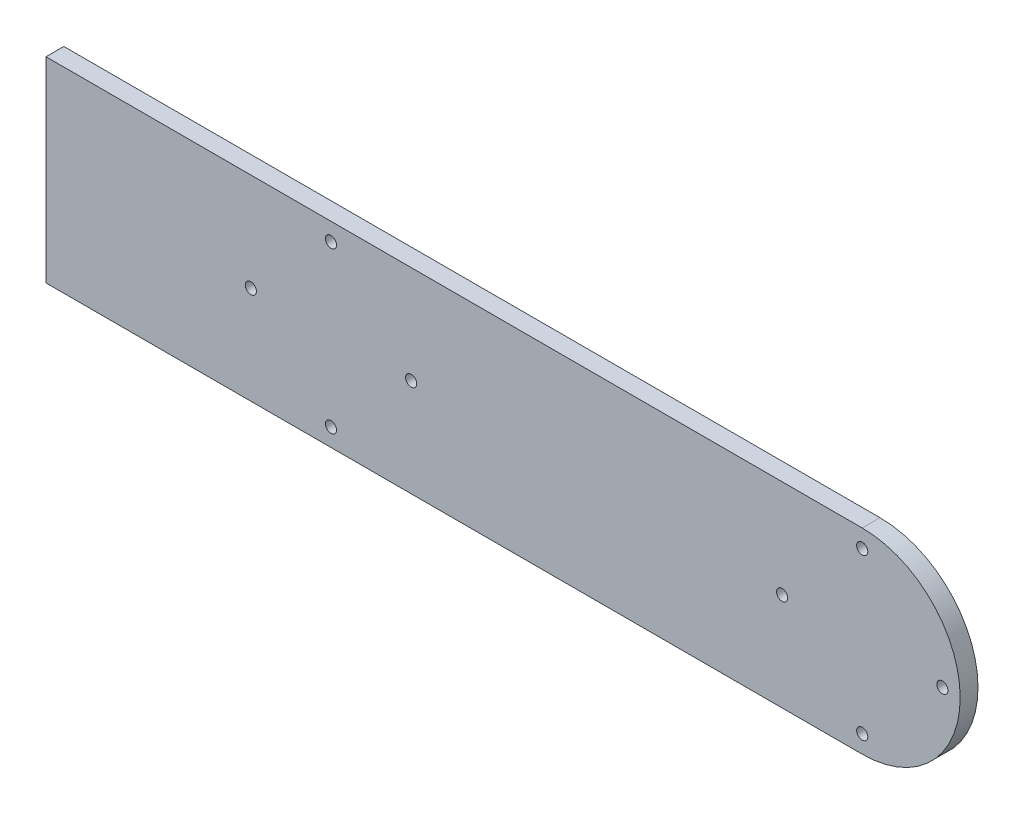
SolidWorks part; units mm, degrees
ref_plane "Front Plane" through (0, 0, 0) normal (0, 0, 1) x (1, 0, 0)
ref_plane "Top Plane" through (0, 0, 0) normal (0, 1, 0) x (1, 0, 0)
ref_plane "Right Plane" through (0, 0, 0) normal (1, 0, 0) x (0, 0, -1)
sketch "Sketch1" plane through (0, 0, 0) normal (0, 1, 0) x (1, 0, 0)
  line L0 (-47.5, -29.9135) -> (47.5, -29.9135) construction
  line L1 (-47.5, 56.6115) -> (47.5, 56.6115) construction
  line L2 (-47.5, 56.6115) -> (-47.5, -56.6115) construction
  line L3 (-47.5, -56.6115) -> (47.5, -56.6115) construction
  line L4 (47.5, 56.6115) -> (47.5, -56.6115) construction
  line L5 (-47.5, 56.6115) -> (47.5, -56.6115) construction
  line L6 (-47.5, -56.6115) -> (47.5, 56.6115) construction
  line L7 (-47.5, -23.9135) -> (47.5, -23.9135) construction
  line L8 (-47.5, 23.5865) -> (47.5, 23.5865) construction
  line L9 (47.5, 27.5865) -> (-47.5, 27.5865) construction
  line L10 (97.198, 47.5) -> (97.198, -47.5) construction
  line L11 (183.723, 47.5) -> (183.723, -47.5) construction
  line L12 (183.723, 47.5) -> (70.5, 47.5) construction
  line L13 (70.5, 47.5) -> (70.5, -47.5) construction
  line L14 (183.723, -47.5) -> (70.5, -47.5) construction
  line L15 (183.723, 47.5) -> (70.5, -47.5) construction
  line L16 (70.5, 47.5) -> (183.723, -47.5) construction
  line L17 (103.198, 47.5) -> (103.198, -47.5) construction
  line L18 (150.698, 47.5) -> (150.698, -47.5) construction
  line L19 (154.698, -47.5) -> (154.698, 47.5) construction
  line L20 (64.5, 88.7731) -> (64.5, -54.5) construction
  line L21 (47.5, -56.6115) -> (-248.4804, -56.6115) construction
  line L22 (47.5, -56.6115) -> (47.5, -62.6115) construction
  line L23 (47.5, -62.6115) -> (-248.4804, -62.6115) construction
  line L24 (-248.4804, -56.6115) -> (-248.4804, -62.6115) construction
  line L25 (64.5, -54.5) -> (327.1082, -54.5) construction
  line L26 (70.5, 94.7731) -> (70.5, -48.5) construction
  line L27 (70.5, -48.5) -> (327.1082, -48.5) construction
  line L28 (70.5, -48.5) -> (70.5, -54.5) construction
  line L29 (70.5, -48.5) -> (64.5, -48.5) construction
  line L30 (47.5, -56.6115) -> (47.5, -62.6115) construction
  line L31 (48.5, 17.5865) -> (48.5, -30) construction
  line L32 (48.5, -30) -> (54.5, -30) construction
  line L33 (54.5, -30) -> (54.5, 23.5865) construction
  line L34 (0, 0) -> (0, 56.6115) construction
  line L35 (-48.5, -30) -> (-54.5, -30) construction
  line L36 (-54.5, -30) -> (-54.5, 23.5865) construction
  line L37 (-48.5, 17.5865) -> (-48.5, -30) construction
  line L38 (54.5, 23.5865) -> (-54.5, 23.5865) construction
  line L39 (-48.5, 17.5865) -> (48.5, 17.5865) construction
  line L40 (48.5, 17.5865) -> (48.5, 23.5865) construction
  line L41 (70.5, 94.7731) -> (-59.952, 94.7731) construction
  line L42 (64.5, 88.7731) -> (-64.5, 88.7731) construction
  line L43 (-64.5, 88.7731) -> (-64.5, -48.5) construction
  line L44 (-64.5, -48.5) -> (-70.5, -48.5) construction
  line L45 (-70.5, -48.5) -> (-70.5, 98.5172) construction
  line L46 (-196.6321, -56.6115) -> (-196.6321, 23.9185) construction
  line L51 (-196.6321, -62.6115) -> (-101.6321, -62.6115) construction
  line L52 (-196.6321, -62.6115) -> (-196.6321, -89.3115) construction
  line L53 (-196.6321, -89.3115) -> (-101.6321, -89.3115) construction
  line L54 (-101.6321, -62.6115) -> (-101.6321, -89.3115) construction
  line L55 (-196.6321, 23.9185) -> (-101.6321, 23.9185) construction
  line L56 (-101.6321, 23.9185) -> (-101.6321, -56.6115) construction
  line L57 (-54.5, -23.9135) -> (-64.5, -23.9135) construction
  line L58 (54.5, -23.9135) -> (64.5, -23.9135) construction
  line L59 (64.5, 88.7731) -> (64.5, 94.7731) construction
  point P0 (0, 0)
  point P17 (127.1115, 0)
  dimension "D1" = 113.223
  dimension "D2" = 95
  dimension "D3" = 6
  dimension "D4" = 26.698
  dimension "D5" = 4
  dimension "D6" = 57.5
  dimension "D7" = 29.025
  dimension "D8" = 6
  dimension "D9" = 95
  dimension "D10" = 6
  dimension "D11" = 26.698
  dimension "D12" = 4
  dimension "D13" = 29.025
  dimension "D14" = 57.5
  dimension "D15" = 30
  dimension "D16" = 1
  dimension "D17" = 1
  dimension "D18" = 10
  dimension "D19" = 26.7
  dimension "D20" = 80.53
sketch "Sketch2" plane through (0, 0, 0) normal (0, 0, 1) x (1, 0, 0)
  line L0 (-47.5, 0) -> (47.5, 0) construction
  line L1 (-47.5, -50) -> (47.5, -50) construction
  line L2 (-47.5, -50) -> (-47.5, 50) construction
  line L3 (-47.5, 50) -> (47.5, 50) construction
  line L4 (47.5, -50) -> (47.5, 50) construction
  line L5 (-47.5, -50) -> (47.5, 50) construction
  line L6 (-47.5, 50) -> (47.5, -50) construction
  line L11 (0, 0) -> (0, 22.5) construction
  line L12 (-196.6321, 0) -> (-101.6321, 0) construction
  line L13 (-196.6321, 0) -> (-101.6321, 0) construction
  line L14 (0, 27.5) -> (-229.1321, 27.5)
  line L15 (-229.1321, 27.5) -> (-229.1321, -27.5)
  line L16 (-229.1321, -27.5) -> (0, -27.5)
  circle A0 centre (0, 0) radius 22.5 construction
  circle A1 centre (0, 22.5) radius 1.5635
  circle A2 centre (22.5, 0) radius 1.5635
  circle A3 centre (0, -22.5) radius 1.5635
  circle A4 centre (-22.5, 0) radius 1.5635
  circle A5 centre (-171.6321, 0) radius 1.5635
  circle A6 centre (-149.1321, 0) radius 22.5 construction
  circle A7 centre (-149.1321, 22.5) radius 1.5635
  circle A8 centre (-126.6321, 0) radius 1.5635
  circle A9 centre (-149.1321, -22.5) radius 1.5635
  arc A10 (0, 27.5) -> (0, -27.5) centre (0, 0) cw
  point P0 (0, 0)
  point P14 (-188.0045, -33.6176)
  point P15 (0, 0)
  point P18 (0, 0)
  point P21 (0, 0)
  point P24 (0, 0)
  dimension "D3" = 45
  dimension "D4" = 3.127
  dimension "D7" = 5
  dimension "D1" = 100
  dimension "D2" = 95
  dimension "D8" = 80
  dimension "D6" = 2
  dimension "D5" = 4
extrude "Boss-Extrude1" add sketch "Sketch2" along normal blind 5
